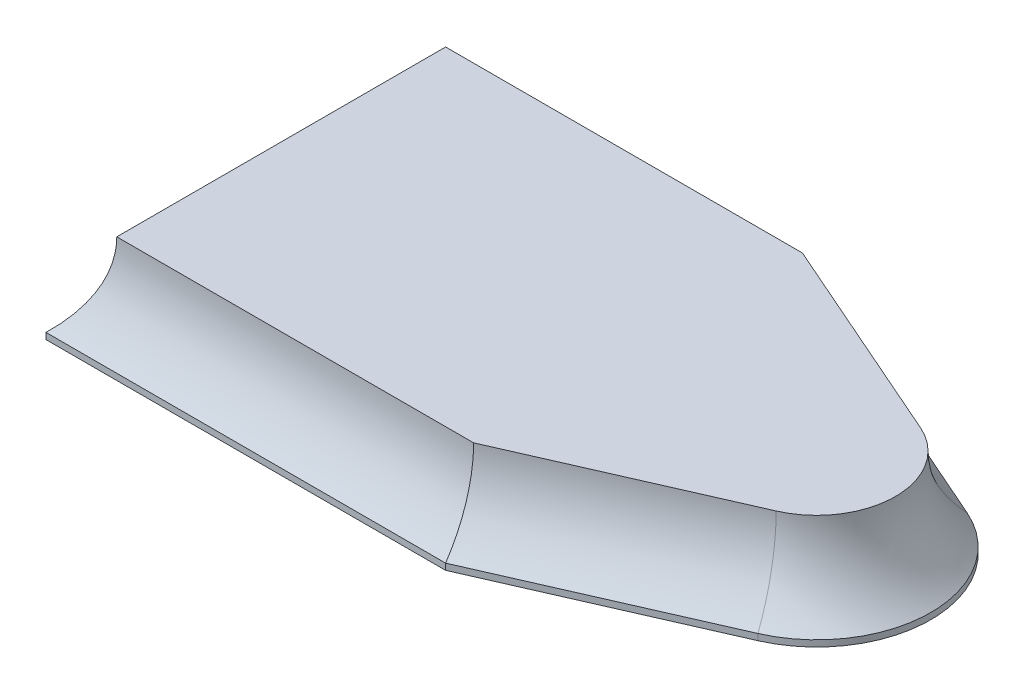
SolidWorks part; units mm, degrees
ref_plane "Front Plane" through (0, 0, 0) normal (0, 0, 1) x (1, 0, 0)
ref_plane "Top Plane" through (0, 0, 0) normal (0, 1, 0) x (1, 0, 0)
ref_plane "Right Plane" through (0, 0, 0) normal (1, 0, 0) x (0, 0, -1)
sketch "Sketch1" plane through (0, 0, 0) normal (0, 1, 0) x (1, 0, 0)
  line L1 (7, 7) -> (10.8034, 5.3315)
  line L2 (0, 0) -> (7, 0)
  line L3 (0, 0) -> (0, 7)
  line L4 (0, 7) -> (7, 7)
  line L7 (7, 0) -> (10.8034, 1.6685)
  arc A0 (10.8034, 1.6685) -> (10.8034, 5.3315) centre (10, 3.5) ccw
  dimension "D3" = 4
  dimension "D1" = 7
  dimension "D2" = 7
  dimension "D4" = 10
sketch "Sketch2" plane through (0, 0, 0) normal (1, 0, 0) x (0, 0, -1)
  line L0 (0, 0) -> (0, 0.11)
  line L1 (0, 0) -> (0.44, 0)
  line L2 (0, 0) -> (7, 0) construction
  line L3 (0.44, 0) -> (0.88, 1.12)
  line L4 (0.88, 1.12) -> (1.88, 1.12)
  line L5 (1.88, 1.12) -> (1.88, 1.56)
  line L6 (1.88, 1.56) -> (0.62, 1.56)
  arc A0 (0, 0.11) -> (0.62, 1.56) centre (-1.38, 1.5576) ccw
  dimension "D7" = 2
  dimension "D1" = 0.11
  dimension "D2" = 0.44
  dimension ".44" = 0.44
  dimension "D3" = 1
  dimension "D4" = 0.44
  dimension "D5" = 0.62
  dimension "D6" = 1.56
sweep "Sweep2" add profiles "Sketch2" path "Sketch1"
sketch "Sketch9" plane through (0, 1.56, 0) normal (0, 1, 0) x (1, 0, 0)
  line L0 (6.6058, 1.88) -> (10.0482, 3.3901) construction
  line L1 (10.0482, 3.6099) -> (6.6058, 5.12) construction
  line L2 (6.6058, 5.12) -> (1.88, 5.12) construction
  line L3 (1.88, 5.12) -> (1.88, 1.88) construction
  line L4 (1.88, 1.88) -> (6.6058, 1.88) construction
  line L5 (6.6058, 1.88) -> (10.0482, 3.3901)
  line L6 (10.0482, 3.6099) -> (6.6058, 5.12)
  line L7 (6.6058, 5.12) -> (1.88, 5.12)
  line L8 (1.88, 5.12) -> (1.88, 1.88)
  line L9 (1.88, 1.88) -> (6.6058, 1.88)
  arc A0 (10.0482, 3.3901) -> (10.0482, 3.6099) centre (10, 3.5) ccw construction
  arc A1 (10.0482, 3.3901) -> (10.0482, 3.6099) centre (10, 3.5) ccw
extrude "Boss-Extrude1" add sketch "Sketch9" against normal blind 0.44
